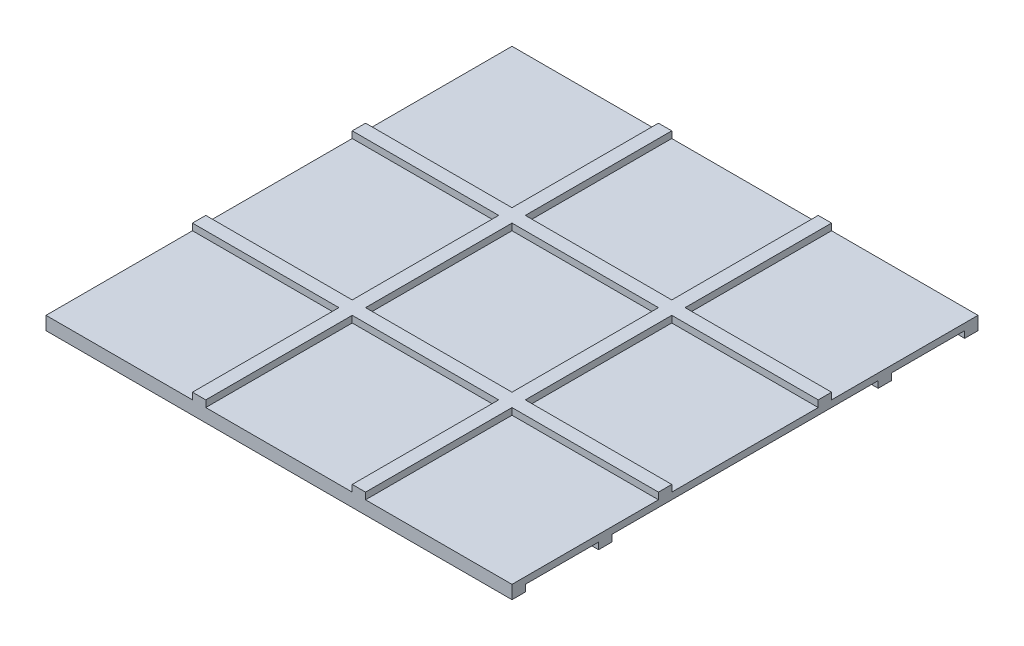
SolidWorks part; units mm, degrees
ref_plane "Alzado" through (0, 0, 0) normal (0, 0, 1) x (1, 0, 0)
ref_plane "Planta" through (0, 0, 0) normal (0, 1, 0) x (1, 0, 0)
ref_plane "Vista lateral" through (0, 0, 0) normal (1, 0, 0) x (0, 0, -1)
sketch "Croquis1" plane through (0, 0, 0) normal (0, 1, 0) x (1, 0, 0)
  line L1 (0, 0) -> (350, 0)
  line L2 (0, 0) -> (0, 350)
  line L3 (0, 350) -> (350, 350)
  line L4 (350, 0) -> (350, 350)
  dimension "D1" = 350
extrude "Saliente-Extruir1" add sketch "Croquis1" along normal blind 5
sketch "Croquis2" plane through (0, 0, 0) normal (0, -1, 0) x (1, 0, 0)
  line L0 (350, 0) -> (350, -350) construction
  line L1 (0, 0) -> (350, 0)
  line L2 (0, 0) -> (0, -10)
  line L3 (0, -10) -> (350, -10)
  line L4 (350, 0) -> (350, -10)
  line L5 (0, -350) -> (0, 0) construction
  line L6 (0, -350) -> (350, -350)
  line L7 (0, -350) -> (0, -340)
  line L8 (0, -340) -> (350, -340)
  line L9 (350, -350) -> (350, -340)
  line L10 (0, -65) -> (350, -65)
  line L11 (0, -65) -> (0, -75)
  line L12 (0, -75) -> (350, -75)
  line L13 (350, -65) -> (350, -75)
  line L14 (350, -175) -> (50350, -175) construction
  line L15 (0, -275) -> (350, -275)
  line L16 (0, -275) -> (0, -285)
  line L17 (0, -285) -> (350, -285)
  line L18 (350, -275) -> (350, -285)
  point P24 (350, -175)
  dimension "D1" = 10
  dimension "D2" = 100
  dimension "D3" = 100
extrude "Saliente-Extruir2" add sketch "Croquis2" along normal blind 5
sketch "Croquis3" plane through (0, 5, 0) normal (0, 1, 0) x (1, 0, 0)
  line L0 (110, 350) -> (120, 350)
  line L1 (0, 350) -> (350, 350) construction
  line L2 (120, 350) -> (120, 240)
  line L3 (120, 240) -> (230, 240)
  line L4 (230, 240) -> (230, 350)
  line L5 (230, 350) -> (240, 350)
  line L6 (240, 350) -> (240, 240)
  line L7 (240, 240) -> (350, 240)
  line L8 (350, 0) -> (350, 350) construction
  line L9 (350, 240) -> (350, 230)
  line L10 (350, 230) -> (240, 230)
  line L11 (240, 230) -> (240, 120)
  line L12 (240, 120) -> (350, 120)
  line L13 (350, 120) -> (350, 110)
  line L14 (350, 110) -> (240, 110)
  line L15 (240, 110) -> (240, 0)
  line L16 (0, 0) -> (350, 0) construction
  line L17 (240, 0) -> (230, 0)
  line L18 (230, 0) -> (230, 110)
  line L19 (230, 110) -> (120, 110)
  line L20 (120, 110) -> (120, 0)
  line L21 (120, 0) -> (110, 0)
  line L22 (110, 350) -> (110, 240)
  line L23 (110, 240) -> (0, 240)
  line L24 (0, 350) -> (0, 0) construction
  line L25 (0, 110) -> (0, 120)
  line L26 (0, 120) -> (110, 120)
  line L27 (0, 240) -> (0, 230)
  line L28 (0, 230) -> (110, 230)
  line L29 (110, 230) -> (110, 120)
  line L30 (0, 110) -> (110, 110)
  line L31 (110, 110) -> (110, 0)
  line L32 (120, 120) -> (120, 230)
  line L33 (120, 230) -> (230, 230)
  line L34 (230, 230) -> (230, 120)
  line L35 (230, 120) -> (120, 120)
  dimension "D1" = 10
extrude "Saliente-Extruir3" add sketch "Croquis3" along normal blind 5
